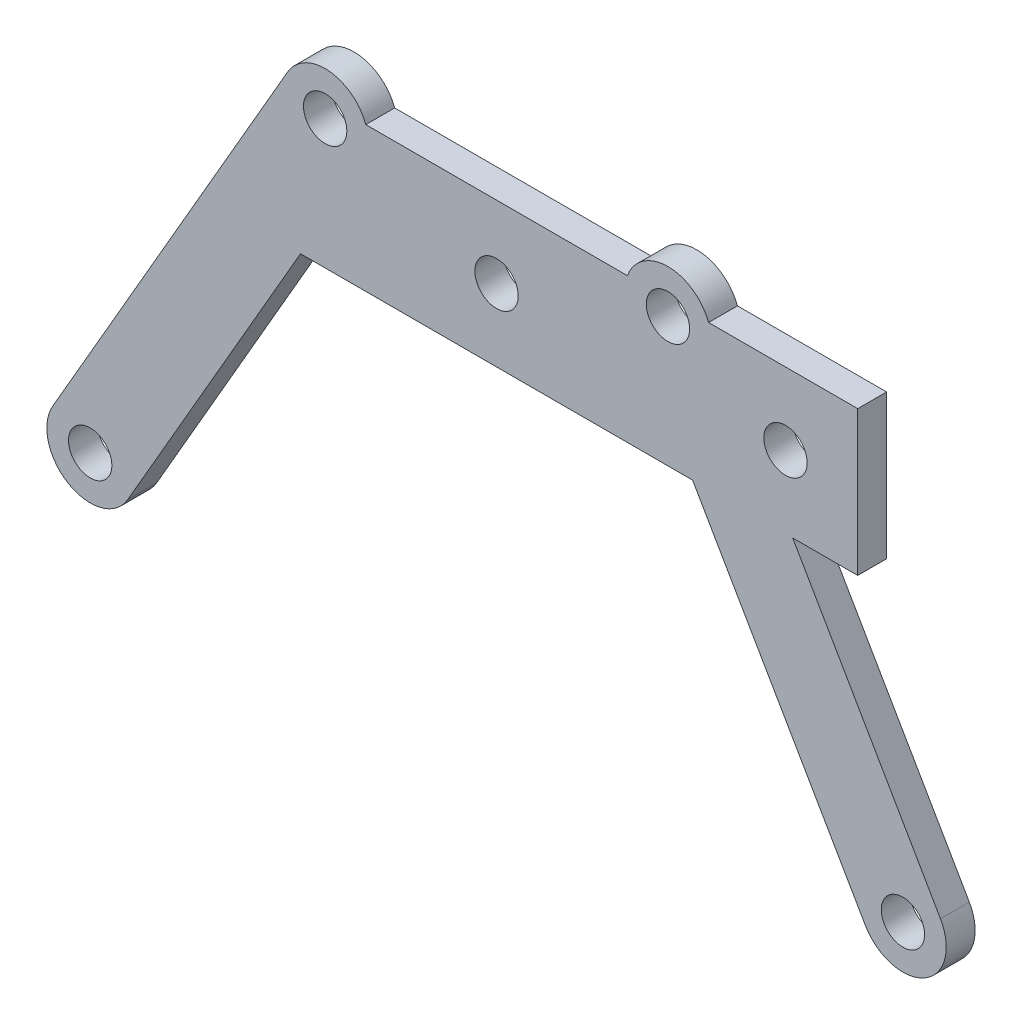
SolidWorks part; units mm, degrees
ref_plane "前视基准面" through (0, 0, 0) normal (0, 0, 1) x (1, 0, 0)
ref_plane "上视基准面" through (0, 0, 0) normal (0, 1, 0) x (1, 0, 0)
ref_plane "右视基准面" through (0, 0, 0) normal (1, 0, 0) x (0, 0, -1)
sketch "草图1" plane through (0, 0, 0) normal (0, 0, 1) x (1, 0, 0)
  line L0 (0, 0) -> (20, 0) construction
  line L2 (-5, 5) -> (25, 5)
  line L3 (-5, 5) -> (-5, -5)
  line L4 (-5, -5) -> (25, -5)
  line L5 (25, 5) -> (25, -5)
  circle A0 centre (0, 0) radius 1.5
  circle A1 centre (20, 0) radius 1.5
  dimension "D2" = 3
  dimension "D1" = 20
  dimension "D3" = 5
  dimension "D4" = 5
  dimension "D5" = 5
  dimension "D6" = 5
extrude "凸台-拉伸1" add sketch "草图1" along normal blind 2
sketch "草图4" plane through (0, 0, 0) normal (0, 0, -1) x (-1, 0, 0)
  line L0 (-30.7257, -22.7175) -> (-20.4965, -5)
  line L1 (5, -5) -> (-25, -5) construction
  line L2 (-25.5296, -25.7175) -> (-13.5683, -5)
  line L3 (-13.5683, -5) -> (-20.4965, -5)
  line L4 (-25, 5) -> (5, 5) construction
  line L5 (-14.6748, 5) -> (-12.9374, 5)
  line L6 (-9.0524, 5) -> (-10.7898, 5)
  line L7 (5, 5) -> (9.0524, 5)
  line L8 (30.7257, -22.7175) -> (14.4617, 5.4526)
  line L9 (25.5296, -25.7175) -> (13.5683, -5)
  line L10 (5, -5) -> (13.5683, -5)
  line L11 (5, 5) -> (5, -5)
  arc A0 (-10.7898, 5) -> (-12.9374, 5) centre (-11.8636, 3.9526) ccw
  circle A1 centre (-28.1276, -24.2175) radius 1.5
  circle A2 centre (11.8636, 3.9526) radius 1.5
  circle A3 centre (28.1276, -24.2175) radius 1.5
  arc A4 (-25.5296, -25.7175) -> (-30.7257, -22.7175) centre (-28.1276, -24.2175) cw
  arc A5 (-9.0524, 5) -> (-14.6748, 5) centre (-11.8636, 3.9526) ccw
  arc A6 (14.4617, 5.4526) -> (9.0524, 5) centre (11.8636, 3.9526) ccw
  arc A7 (30.7257, -22.7175) -> (25.5296, -25.7175) centre (28.1276, -24.2175) cw
  dimension "D1" = 3
  dimension "D2" = 3
  dimension "D4" = 3
  dimension "D3" = 3
extrude "凸台-拉伸3" add sketch "草图4" against normal up to surface (2 mm away) up to face at (1.5, 0, 2)
sketch "草图5" plane through (0, 0, 0) normal (0, 0, -1) x (-1, 0, 0)
  circle A0 centre (-11.8636, 3.9526) radius 1.5
extrude "切除-拉伸2" cut sketch "草图5" against normal through all
